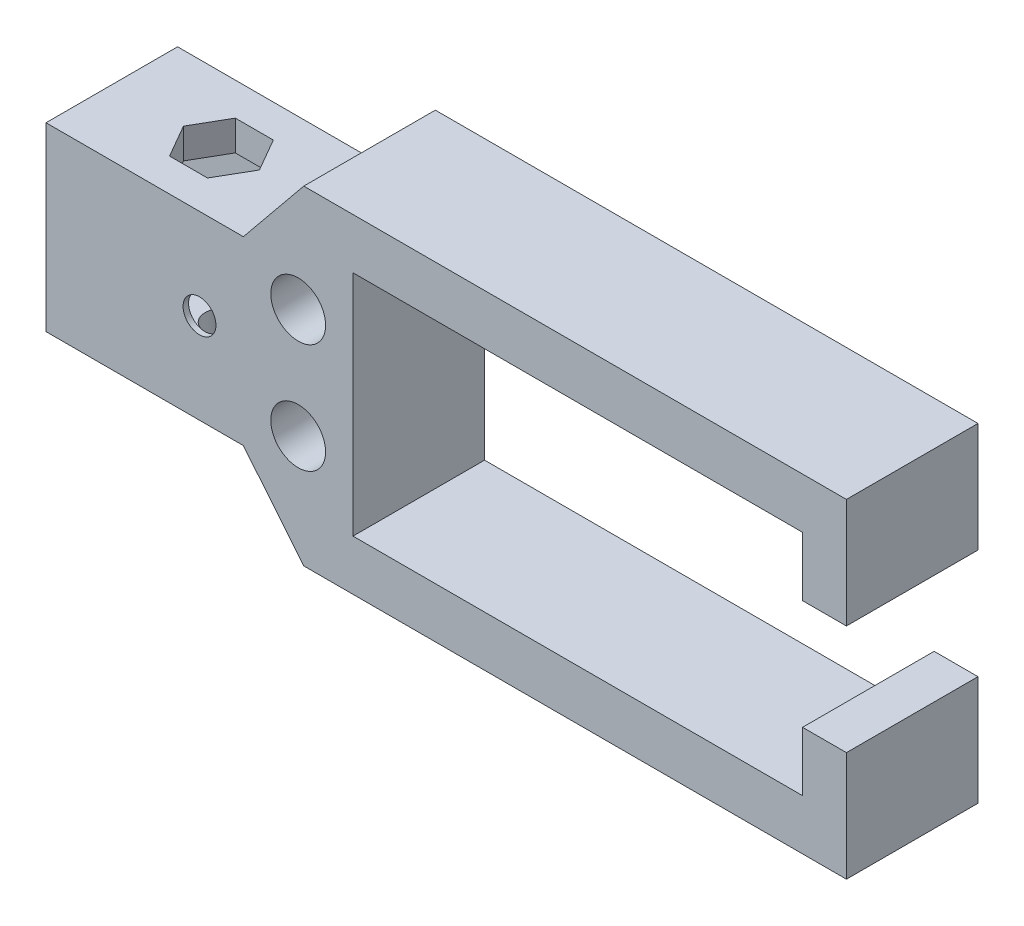
SolidWorks part; units mm, degrees
ref_plane "前视基准面" through (0, 0, 0) normal (0, 0, 1) x (1, 0, 0)
ref_plane "上视基准面" through (0, 0, 0) normal (0, 1, 0) x (1, 0, 0)
ref_plane "右视基准面" through (0, 0, 0) normal (1, 0, 0) x (0, 0, -1)
sketch "草图2" plane through (0, 0, 0) normal (0, 0, 1) x (1, 0, 0)
  line L0 (-15.25, 10.25) -> (15.25, 10.25)
  line L1 (-11.25, 6.25) -> (11.25, 6.25)
  line L2 (-11.25, 6.25) -> (-11.25, -6.25)
  line L3 (-11.25, -6.25) -> (11.25, -6.25)
  line L4 (11.25, 6.25) -> (11.25, -6.25)
  line L5 (-11.25, 6.25) -> (11.25, -6.25) construction
  line L6 (-11.25, -6.25) -> (11.25, 6.25) construction
  line L11 (-10.2, 6.25) -> (10.2, -6.25) construction
  line L12 (-10.2, -6.25) -> (10.2, 6.25) construction
  line L13 (15.25, 10.25) -> (15.25, -10.25)
  line L14 (-15.25, -10.25) -> (15.25, -10.25)
  line L15 (-15.25, 10.25) -> (-15.25, -10.25)
  point P0 (0, 0)
  point P5 (0, 0)
  dimension "D1" = 12.5
  dimension "D2" = 22.5
  dimension "D3" = 4
extrude "凸台-拉伸1" add sketch "草图2" along normal blind 12
sketch "草图3" plane through (0, 0, 12) normal (0, 0, 1) x (1, 0, 0)
  line L0 (0, 0) -> (0, 5) construction
  line L1 (-15.25, 5) -> (-18, 5)
  line L2 (-15.25, 10.25) -> (-15.25, -10.25) construction
  line L3 (-18, 5) -> (-18, -5)
  line L4 (-18, -5) -> (-15.25, -5)
  line L5 (-15.25, -5) -> (-15.25, 5)
  point P8 (-15.25, 0)
  point P10 (-16.625, -5)
  dimension "D1" = 36
  dimension "D2" = 10
extrude "凸台-拉伸2" add sketch "草图3" against normal blind 3
mirror "镜向1" about plane through (0, 0, 0) normal (1, 0, 0) of "凸台-拉伸2"
sketch "草图4" plane through (0, 0, 0) normal (0, 0, -1) x (-1, 0, 0)
  line L0 (0, 0) -> (8.8535, 0) construction
  line L1 (12.75, -5) -> (17.6907, -5)
  line L2 (12.75, -5) -> (12.75, 5)
  line L3 (12.75, 5) -> (17.6907, 5)
  line L4 (17.6907, -5) -> (17.6907, 5)
  line L5 (11.25, 6.25) -> (11.25, -6.25) construction
  dimension "D1" = 10
  dimension "D2" = 1.5
extrude "切除-拉伸1" cut sketch "草图4" against normal up to surface (9 mm away) up to face at (-16.625, 0, 9)
mirror "镜向2" about plane through (0, 0, 0) normal (1, 0, 0) of "切除-拉伸1"
sketch "草图5" plane through (-18, 0, 0) normal (-1, 0, 0) x (0, 0, 1)
  line L0 (12, 10.25) -> (12, 5) construction
  line L1 (12, 5) -> (12, -5) construction
  line L2 (12, -5) -> (12, -10.25) construction
  line L3 (12, -10.25) -> (0, -10.25) construction
  line L4 (0, -5) -> (0, -10.25) construction
  line L5 (0, 5) -> (0, -5) construction
  line L6 (0, 10.25) -> (0, 5) construction
  line L7 (12, 10.25) -> (0, 10.25) construction
  line L8 (12, 10.25) -> (12, 5)
  line L9 (12, 5) -> (12, -5)
  line L10 (12, -5) -> (12, -10.25)
  line L11 (12, -10.25) -> (0, -10.25)
  line L12 (0, -5) -> (0, -10.25)
  line L13 (0, 5) -> (0, -5)
  line L14 (0, 10.25) -> (0, 5)
  line L15 (12, 10.25) -> (0, 10.25)
extrude "凸台-拉伸3" add sketch "草图5" along normal blind 20
sketch "草图6" plane through (-15.25, 0, 0) normal (-1, 0, 0) x (0, 0, 1)
  line L5 (12, -5) -> (9, -5)
  line L6 (9, -5) -> (0, -5)
  line L7 (0, -5) -> (0, -10.25)
  line L8 (0, -10.25) -> (12, -10.25)
  line L9 (12, -10.25) -> (12, -5)
  line L10 (12, -5) -> (9, -5)
  line L11 (9, -5) -> (0, -5)
  line L12 (0, -5) -> (0, -10.25)
  line L13 (0, -10.25) -> (12, -10.25)
  line L14 (12, -10.25) -> (12, -5)
  dimension "D1" = 0
extrude "凸台-拉伸4" add sketch "草图6" along normal up to next
mirror "镜向3" about plane through (0, 0, 0) normal (0, 1, 0) of "凸台-拉伸4"
sketch "草图7" plane through (0, 0, 9) normal (0, 0, -1) x (-1, 0, 0)
  circle A0 centre (15.4879, 2.2966) radius 1.2527
extrude "切除-拉伸2" cut sketch "草图7" against normal through all
sketch "草图8" plane through (-38, 0, 0) normal (-1, 0, 0) x (0, 0, 1)
  line L0 (6, 10.25) -> (6, 4.7611) construction
  line L1 (1, -5) -> (11, -5)
  line L2 (1, -5) -> (1, 5)
  line L3 (1, 5) -> (11, 5)
  line L4 (11, -5) -> (11, 5)
  line L5 (12, 10.25) -> (0, 10.25) construction
  line L6 (0, 0) -> (4.6816, 0) construction
  dimension "D1" = 10
  dimension "D2" = 10
extrude "切除-拉伸3" cut sketch "草图8" against normal blind 18
sketch "草图10" plane through (0, 0, 0) normal (0, 0, -1) x (-1, 0, 0)
  line L0 (-15.25, 10.25) -> (38, 10.25) construction
  line L1 (20, 8.25) -> (43.1061, 8.25)
  line L2 (20, 8.25) -> (20, 16.0046)
  line L3 (20, 16.0046) -> (43.1061, 16.0046)
  line L4 (43.1061, 8.25) -> (43.1061, 16.0046)
  line L5 (38, 10.25) -> (38, -10.25) construction
  dimension "D1" = 2
  dimension "D2" = 18
extrude "切除-拉伸4" cut sketch "草图10" against normal through all
mirror "镜向4" about plane through (0, 0, 0) normal (0, 1, 0) of "切除-拉伸4"
sketch "草图11" plane through (0, -8.25, 0) normal (0, -1, 0) x (1, 0, 0)
  line L0 (-38, 6) -> (-41.4159, 6) construction
  line L2 (-29.5, 6) -> (-24.3196, 6) construction
  line L3 (-20, 12) -> (-20, 0) construction
  line L4 (-38, 0) -> (-38, 12) construction
  circle A1 centre (-28, 6) radius 1.5
  dimension "D1" = 3
  dimension "D3" = 8
extrude "切除-拉伸5" cut sketch "草图11" against normal through all
mirror "镜向5" about plane through (0, 0, 0) normal (1, 0, 0) of "切除-拉伸2"
sketch "草图12" plane through (-38, 0, 0) normal (-1, 0, 0) x (0, 0, 1)
  line L0 (11, 5) -> (1, 5) construction
  line L1 (0.5, -5.5) -> (11.5, -5.5)
  line L2 (0.5, -5.5) -> (0.5, 5.5)
  line L3 (0.5, 5.5) -> (11.5, 5.5)
  line L4 (11.5, -5.5) -> (11.5, 5.5)
  line L5 (11, -5) -> (11, 5) construction
  line L6 (1, 5) -> (1, -5) construction
  line L7 (1, -5) -> (11, -5) construction
  dimension "D1" = 0.5
  dimension "D2" = 0.5
  dimension "D3" = 0.5
  dimension "D4" = 0.5
extrude "切除-拉伸6" cut sketch "草图12" against normal up to surface (18 mm away) up to face at (-20, 0, 6)
sketch "草图13" plane through (0, 0, 12) normal (0, 0, 1) x (1, 0, 0)
  line L0 (11.25, 6.25) -> (-11.25, 6.25) construction
  line L1 (-11.75, -6.75) -> (11.75, -6.75)
  line L2 (-11.75, -6.75) -> (-11.75, 6.75)
  line L3 (-11.75, 6.75) -> (11.75, 6.75)
  line L4 (11.75, -6.75) -> (11.75, 6.75)
  line L5 (-11.75, -6.75) -> (11.75, 6.75) construction
  line L6 (-11.75, 6.75) -> (11.75, -6.75) construction
  line L7 (11.25, -6.25) -> (11.25, 6.25) construction
  point P0 (0, 0)
  dimension "D1" = 0.5
  dimension "D2" = 0.5
extrude "切除-拉伸7" cut sketch "草图13" against normal through all
sketch "草图14" plane through (0, 0, 12) normal (0, 0, 1) x (1, 0, 0)
  line L1 (18, -5) -> (8.8706, -5)
  line L2 (18, -5) -> (18, 5.2189)
  line L3 (18, 5.2189) -> (8.8706, 5.2189)
  line L4 (8.8706, -5) -> (8.8706, 5.2189)
extrude "切除-拉伸8" cut sketch "草图14" against normal through all
sketch "草图15" plane through (0, 0, 12) normal (0, 0, 1) x (1, 0, 0)
  line L0 (0, 0) -> (13.6471, 0) construction
  line L1 (-20, -15) -> (35, -15)
  line L2 (-20, -15) -> (-20, 15)
  line L3 (-20, 15) -> (35, 15)
  line L4 (35, -15) -> (35, 15)
  line L5 (-20, -10.25) -> (-20, -8.25) construction
  dimension "D1" = 30
  dimension "D2" = 55
extrude "凸台-拉伸5" add sketch "草图15" against normal up to surface (12 mm away) up to face at (-15.375, 0, 0)
sketch "草图17" plane through (0, 0, 12) normal (0, 0, 1) x (1, 0, 0)
  line L0 (0, 0) -> (37.6037, 0) construction
  line L1 (35, -5) -> (35, 5)
  line L2 (35, -15) -> (35, 15) construction
  line L3 (35, 5) -> (31, 5)
  line L4 (31, 5) -> (31, 10.4)
  line L5 (31, 10.4) -> (-10, 10.4)
  line L6 (-10, 10.4) -> (-10, -10.4)
  line L7 (31, -10.4) -> (-10, -10.4)
  line L8 (31, -5) -> (31, -10.4)
  line L9 (35, -5) -> (31, -5)
  point P12 (-10, 0)
  point P15 (35, 0)
  dimension "D1" = 41
  dimension "D2" = 4
  dimension "D3" = 10
  dimension "D4" = 20.8
extrude "切除-拉伸9" cut sketch "草图17" against normal through all
sketch "草图18" plane through (0, 0, 0) normal (0, 0, -1) x (-1, 0, 0)
  line L0 (0, 0) -> (30.7811, 0) construction
  line L1 (10, 10.4) -> (10, -10.4) construction
  circle A0 centre (15, -5) radius 2.5
  dimension "D1" = 5
  dimension "D3" = 5
  dimension "D2" = 10
extrude "切除-拉伸10" cut sketch "草图18" against normal through all
mirror "镜向6" about plane through (0, 0, 0) normal (0, 1, 0) of "切除-拉伸10"
sketch "草图19" plane through (0, 0, 0) normal (0, 0, -1) x (-1, 0, 0)
  line L0 (20, 8.25) -> (14.4914, 15)
  line L1 (20, 15) -> (-35, 15) construction
  line L2 (14.4914, 15) -> (20, 15)
  line L3 (20, 15) -> (20, 8.25)
extrude "切除-拉伸11" cut sketch "草图19" against normal through all
mirror "镜向7" about plane through (0, 0, 0) normal (0, 1, 0) of "切除-拉伸11"
sketch "草图20" plane through (0, 8.25, 0) normal (0, 1, 0) x (1, 0, 0)
  line L0 (-20, -12) -> (-20, 0) construction
  line L1 (-26.2679, -3) -> (-29.7321, -3)
  line L2 (-29.7321, -3) -> (-31.4641, -6)
  line L3 (-31.4641, -6) -> (-29.7321, -9)
  line L4 (-29.7321, -9) -> (-26.2679, -9)
  line L5 (-26.2679, -9) -> (-24.5359, -6)
  line L6 (-24.5359, -6) -> (-26.2679, -3)
  circle A0 centre (-28, -6) radius 3 construction
  point P1 (-28, -9)
  dimension "D1" = 6
extrude "切除-拉伸12" cut sketch "草图20" against normal up to next
sketch "草图21" plane through (0, 0, 12) normal (0, 0, 1) x (1, 0, 0)
  line L0 (-20, -5.5) -> (-20, 5.5) construction
  line L1 (-38, 0) -> (-27.4521, 0) construction
  line L2 (-38, -8.25) -> (-38, 8.25) construction
  circle A0 centre (-24, 0) radius 1.5
  dimension "D1" = 3
  dimension "D2" = 4
extrude "切除-拉伸13" cut sketch "草图21" against normal up to next
